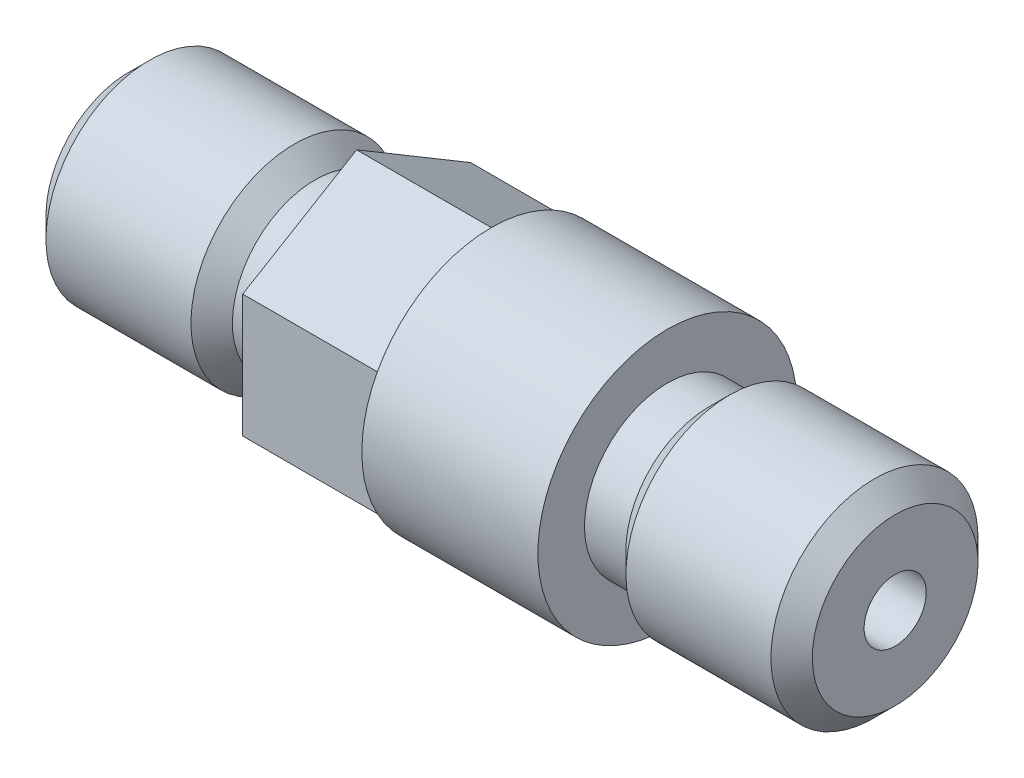
SolidWorks part; units mm, degrees
material "Latão"
ref_plane "Plano frontal" through (0, 0, 0) normal (0, 0, 1) x (1, 0, 0)
ref_plane "Plano superior" through (0, 0, 0) normal (0, 1, 0) x (1, 0, 0)
ref_plane "Plano direito" through (0, 0, 0) normal (1, 0, 0) x (0, 0, -1)
sketch "Esboço1" plane through (0, 0, 0) normal (0, 0, 1) x (1, 0, 0)
  line L0 (0, 0) -> (-19.5, 0)
  line L1 (0, 0) -> (0, 4)
  line L2 (0, 4) -> (-1, 5)
  line L3 (-1, 5) -> (-8, 5)
  line L4 (-8, 5) -> (-9, 4)
  line L5 (-9, 4) -> (-11, 4)
  line L6 (-11, 4) -> (-11, 6.25)
  line L7 (-11, 6.25) -> (-19.5, 6.25)
  line L8 (-19.5, 6.25) -> (-19.5, 0)
  point P10 (-17.4769, 2.983)
  point P11 (-17.6221, 2.8122)
  dimension "D1" = 5
  dimension "D2" = 45
  dimension "D3" = 6.25
  dimension "D4" = 45
  dimension "D5" = 2
  dimension "D6" = 11
  dimension "D7" = 8.5
  dimension "D8" = 1
  dimension "D9" = 1
revolve "Revolução1" add sketch "Esboço1" angle 360 about L0
sketch "Esboço2" plane through (-19.5, 0, 0) normal (-1, 0, 0) x (0, 0, 1)
  line L0 (-5.5, 2.9686) -> (-5.5, -2.9686)
  line L1 (5.5, 2.9686) -> (5.5, -2.9686)
  line L2 (-5.5, -2.9686) -> (0, -6.25)
  line L3 (0, -6.25) -> (5.5, -2.9686)
  line L4 (-5.5, 2.9686) -> (0, 6.25)
  line L5 (0, 6.25) -> (5.5, 2.9686)
  circle A1 centre (0, 0) radius 6.25 construction
  dimension "D1" = 5.5
  dimension "D2" = 5.5
extrude "Ressalto-extrusão1" add sketch "Esboço2" along normal blind 6.5
sketch "Esboço3" plane through (0, 0, 0) normal (0, 0, 1) x (1, 0, 0)
  line L0 (-29, 0) -> (-26, 0)
  line L1 (-26, 4) -> (-26, 0)
  line L2 (-29, 0) -> (-29, 1.7929)
  line L3 (-29, 1.7929) -> (-29.7071, 2.5)
  line L4 (-29.7071, 2.5) -> (-37, 2.5)
  line L5 (-37, 2.5) -> (-37, 4)
  line L6 (-37, 4) -> (-36, 5)
  line L7 (-36, 5) -> (-29, 5)
  line L8 (-29, 5) -> (-28, 4)
  line L9 (-28, 4) -> (-26, 4)
  line L10 (-26, 2.9686) -> (-26, 6.25) construction
  line L11 (-26, -2.9686) -> (-26, 2.9686) construction
  dimension "D1" = 8
  dimension "D2" = 2.5
  dimension "D3" = 2.5
  dimension "D4" = 45
  dimension "D5" = 45
  dimension "D6" = 2
  dimension "D7" = 1
  dimension "D8" = 1
  dimension "D9" = 1
  dimension "D11" = 11
revolve "Revolução2" add sketch "Esboço3" angle 360 about L0
sketch "Esboço4" plane through (-29, 0, 0) normal (-1, 0, 0) x (0, 0, 1)
  circle A0 centre (0, 0) radius 1.5
  dimension "D1" = 3
extrude "Corte-extrusão1" cut sketch "Esboço4" against normal through all
